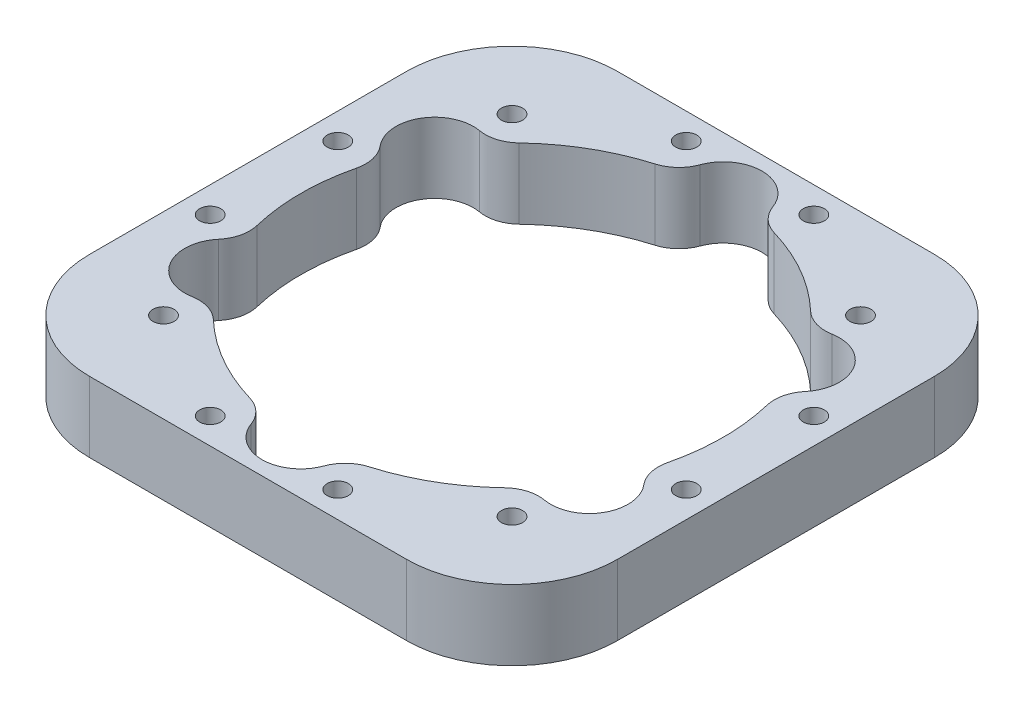
SolidWorks part; units mm, degrees
ref_plane "Front Plane" through (0, 0, 0) normal (0, 0, 1) x (1, 0, 0)
ref_plane "Top Plane" through (0, 0, 0) normal (0, 1, 0) x (1, 0, 0)
ref_plane "Right Plane" through (0, 0, 0) normal (1, 0, 0) x (0, 0, -1)
sketch "Sketch1" plane through (0, 0, 0) normal (0, 1, 0) x (1, 0, 0)
  line L0 (-49.1682, 0) -> (0, 0) construction
  line L1 (0, 0) -> (-48.4521, -12.9827) construction
  line L2 (-37.5, 37.5) -> (37.5, 37.5)
  line L3 (-37.5, 37.5) -> (-37.5, -37.5)
  line L4 (37.5, 37.5) -> (37.5, -37.5)
  line L5 (-37.5, -37.5) -> (37.5, -37.5)
  circle A0 centre (0, 0) radius 37.5 construction
  circle A1 centre (0, 0) radius 35 construction
  circle A2 centre (0, 0) radius 30
  circle A3 centre (0, 30) radius 5.5
  circle A4 centre (25.9808, 15) radius 5.5
  circle A5 centre (25.9808, -15) radius 5.5
  circle A6 centre (0, -30) radius 5.5
  circle A7 centre (-25.9808, -15) radius 5.5
  circle A8 centre (-25.9808, 15) radius 5.5
  circle A9 centre (-33.8074, -9.0587) radius 1.5
  circle A10 centre (-33.8074, 9.0587) radius 1.5
  circle A11 centre (-24.7487, 24.7487) radius 1.5
  circle A12 centre (-9.0587, 33.8074) radius 1.5
  circle A13 centre (9.0587, 33.8074) radius 1.5
  circle A14 centre (24.7487, 24.7487) radius 1.5
  circle A15 centre (33.8074, 9.0587) radius 1.5
  circle A16 centre (33.8074, -9.0587) radius 1.5
  circle A17 centre (24.7487, -24.7487) radius 1.5
  circle A18 centre (9.0587, -33.8074) radius 1.5
  circle A19 centre (-9.0587, -33.8074) radius 1.5
  circle A20 centre (-24.7487, -24.7487) radius 1.5
  point P19 (0, 0)
  point P47 (0, 0)
  dimension "D1" = 75
  dimension "D2" = 70
  dimension "D3" = 60
  dimension "D4" = 11
  dimension "D7" = 3
  dimension "D6" = 15
  dimension "D5" = 6
  dimension "D8" = 12
extrude "Boss-Extrude1" add sketch "Sketch1" along normal blind 10 contours A0 A20 A19 A18 A17 A16 A15 A14 A13 A12 A11 A10 A9 A8 A2 A3 A4 A5 A6 A7
fillet "Fillet1" radius 5 12 edges at (5.4768, 5, -29.4958) (-5.4768, 5, -29.4958) (28.2826, 5, -10.0048) (22.8057, 5, -19.491) (22.8057, 5, 19.491) (28.2826, 5, 10.0048) (-5.4768, 5, 29.4958) (5.4768, 5, 29.4958) (-28.2826, 5, 10.0048) (-22.8057, 5, 19.491) (-22.8057, 5, -19.491) (-28.2826, 5, -10.0048)
fillet "Fillet2" radius 15 4 edges at (-37.5, 5, 37.5) (37.5, 5, 37.5) (37.5, 5, -37.5) (-37.5, 5, -37.5)
